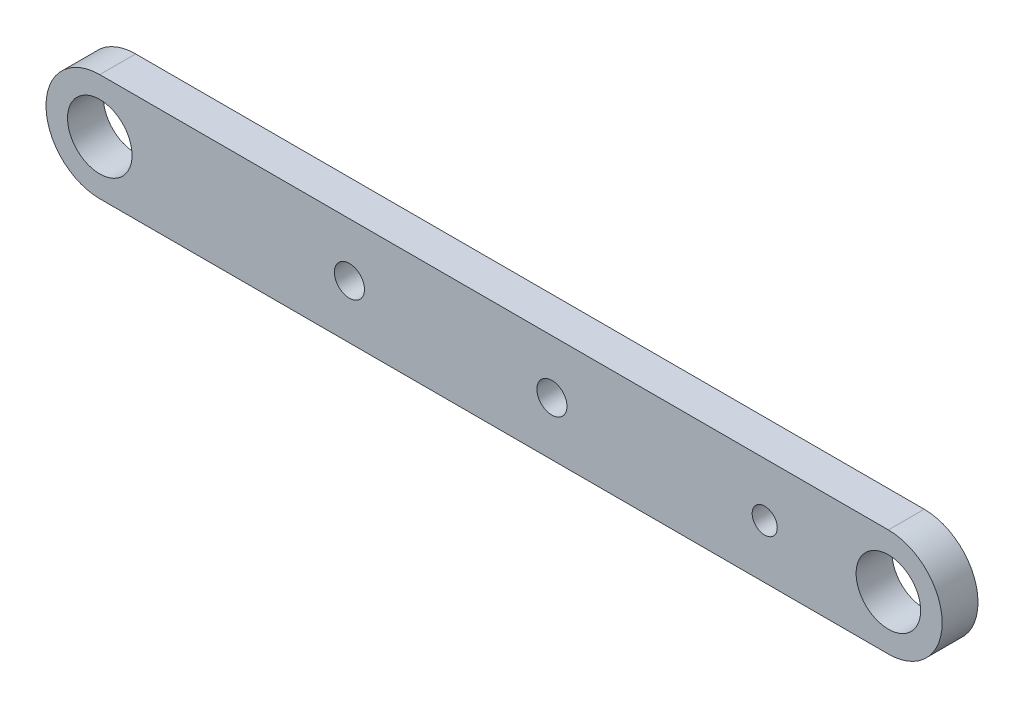
SolidWorks part; units mm, degrees
ref_plane "Plan de face" through (0, 0, 0) normal (0, 0, 1) x (1, 0, 0)
ref_plane "Plan de dessus" through (0, 0, 0) normal (0, 1, 0) x (1, 0, 0)
ref_plane "Plan de droite" through (0, 0, 0) normal (1, 0, 0) x (0, 0, -1)
sketch "Esquisse1" plane through (0, 0, 0) normal (0, 0, 1) x (1, 0, 0)
  line L0 (-110, 0) -> (0, 0) construction
  line L1 (-110, 7.5) -> (0, 7.5)
  line L2 (-110, -7.5) -> (0, -7.5)
  circle A0 centre (0, 0) radius 4.5
  circle A1 centre (-110, 0) radius 4.5
  arc A2 (-110, 7.5) -> (-110, -7.5) centre (-110, 0) ccw
  arc A3 (0, -7.5) -> (0, 7.5) centre (0, 0) ccw
  circle A4 centre (-75.18, 0) radius 2.1
  circle A5 centre (-46.93, 0) radius 2.1
  circle A6 centre (-17.25, 0) radius 1.75
  point P5 (-55, 0)
  point P10 (0, 4.5)
  dimension "D1" = 9
  dimension "D4" = 3.5
  dimension "D5" = 4.2
  dimension "D6" = 28.25
  dimension "D2" = 110
  dimension "D3" = 3
  dimension "D7" = 34.82
  dimension "D8" = 17.25
extrude "Boss.-Extru.1" add sketch "Esquisse1" along normal blind 5
